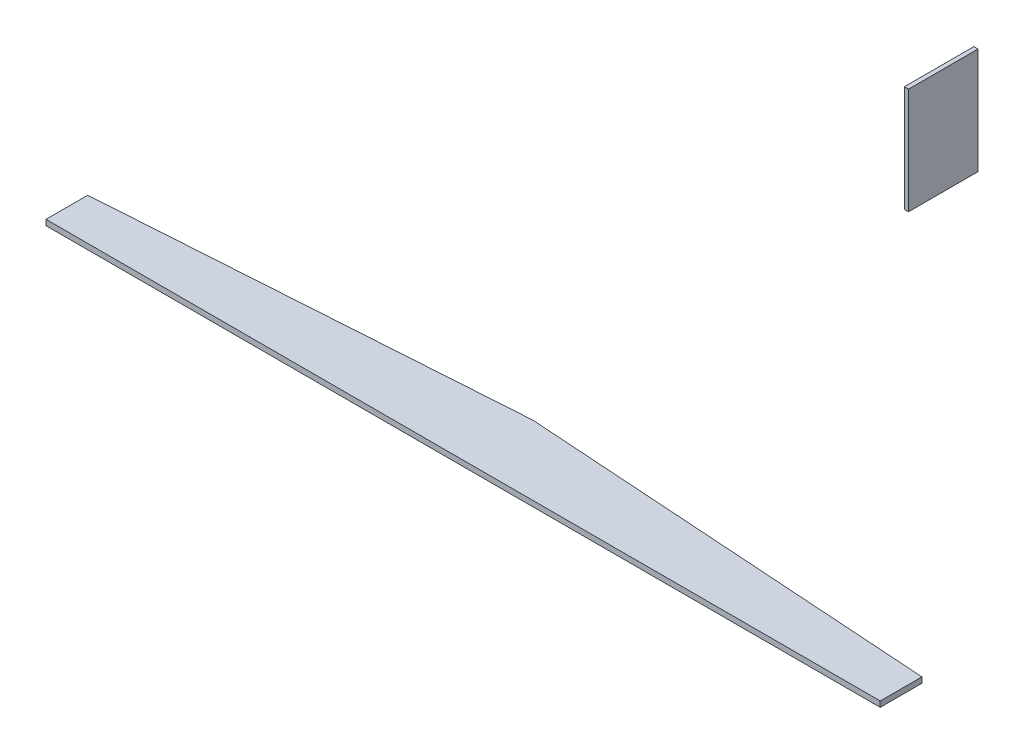
SolidWorks part; units mm, degrees
material "Default"
ref_plane "Front Plane" through (0, 0, 0) normal (0, 0, 1) x (1, 0, 0)
ref_plane "Top Plane" through (0, 0, 0) normal (0, 1, 0) x (1, 0, 0)
ref_plane "Right Plane" through (0, 0, 0) normal (1, 0, 0) x (0, 0, -1)
sketch "Sketch1" plane through (0, 0, 0) normal (1, 0, 0) x (0, 0, -1)
  line L0 (-150, 10) -> (150, -10) construction
  line L1 (-150, 10) -> (150, 10)
  line L2 (-150, 10) -> (-150, -10)
  line L3 (-150, -10) -> (150, -10)
  line L4 (150, 10) -> (150, -10)
  dimension "D1" = 300
  dimension "D2" = 20
sketch "Sketch2" plane through (0, 0, 0) normal (0, 1, 0) x (1, 0, 0)
  line L0 (0, -150) -> (0, 150) construction
  line L1 (0, -94.094) -> (-1500, -94.094)
  line L2 (0, -94.094) -> (0, 155.906)
  line L4 (-1500, -94.094) -> (-1500, 55.906)
  line L5 (0, 155.906) -> (-1500, 55.906)
  dimension "D1" = 250
  dimension "D2" = 150
  dimension "D3" = 1500
extrude "Boss-Extrude3" add sketch "Sketch2" along normal blind 20
mirror "Mirror1" about plane through (0, 20, 94.094) normal (-1, 0, 0) of "Boss-Extrude3"
sketch "Sketch3" plane through (0, 0, 0) normal (0, 1, 0) x (1, 0, 0)
  line L0 (0, 0) -> (0, 1500) construction
  line L1 (-7.5, 1500) -> (7.5, 1500)
  line L2 (-7.5, 1500) -> (-7.5, 1750)
  line L3 (-7.5, 1750) -> (7.5, 1750)
  line L4 (7.5, 1500) -> (7.5, 1750)
  point P7 (0, 0)
  point P8 (0, 0)
  dimension "D1" = 1500
  dimension "D2" = 15
  dimension "D3" = 250
extrude "Boss-Extrude4" add sketch "Sketch3" along normal blind 382 separate body
